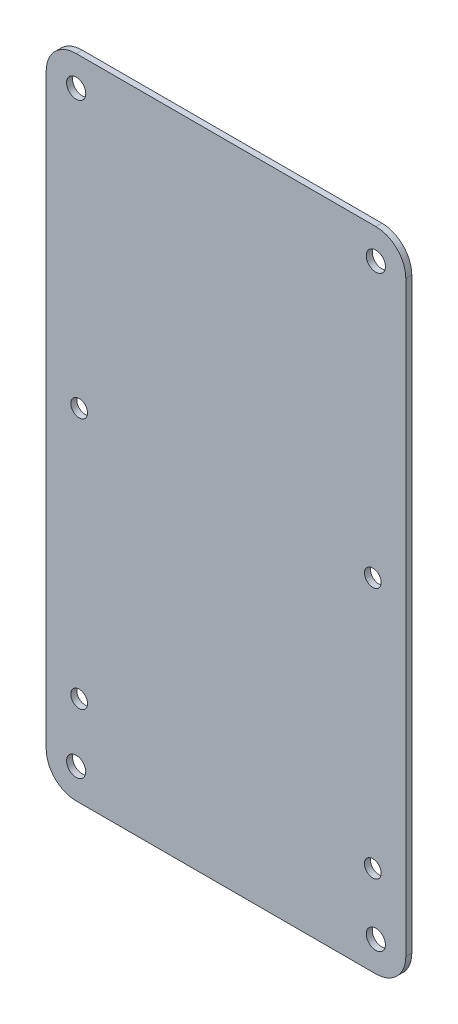
SolidWorks part; units mm, degrees
ref_plane "正面" through (0, 0, 0) normal (0, 0, 1) x (1, 0, 0)
ref_plane "平面" through (0, 0, 0) normal (0, 1, 0) x (1, 0, 0)
ref_plane "右側面" through (0, 0, 0) normal (1, 0, 0) x (0, 0, -1)
sketch "ｽｹｯﾁ1" plane through (0, 0, 0) normal (0, 0, 1) x (1, 0, 0)
  line L1 (-30, 54) -> (30, 54)
  line L2 (-30, 54) -> (-30, -54)
  line L3 (-30, -54) -> (30, -54)
  line L4 (30, 54) -> (30, -54)
  line L5 (-30, 54) -> (30, -54) construction
  line L6 (-30, -54) -> (30, 54) construction
  point P0 (0, 0)
  dimension "D1" = 60
  dimension "D2" = 108
extrude "ﾎﾞｽ - 押し出し1" add sketch "ｽｹｯﾁ1" along normal blind 1
sketch "ｽｹｯﾁ4" plane through (0, 0, 1) normal (0, 0, 1) x (1, 0, 0)
  line L0 (-30, -54) -> (30, -54) construction
  line L1 (-24.5, 3) -> (24.5, 3) construction
  line L2 (-24.5, 3) -> (-24.5, -39) construction
  line L3 (-24.5, -39) -> (24.5, -39) construction
  line L4 (24.5, 3) -> (24.5, -39) construction
  circle A0 centre (-24.5, 3) radius 1.4
  circle A1 centre (-24.5, -39) radius 1.4
  circle A2 centre (24.5, 3) radius 1.4
  circle A3 centre (24.5, -39) radius 1.4
  point P4 (0, -39)
  point P7 (0, -54)
  dimension "D5" = 2.8
  dimension "D6" = 2.8
  dimension "D7" = 2.8
  dimension "D8" = 2.8
  dimension "D1" = 49
  dimension "D2" = 42
  dimension "D3" = 0
  dimension "D4" = 15
extrude "ｶｯﾄ - 押し出し2" cut sketch "ｽｹｯﾁ4" against normal blind 10
sketch "ｽｹｯﾁ9" plane through (0, 0, 1) normal (0, 0, 1) x (1, 0, 0)
  line L0 (30, -54) -> (30, 54) construction
  line L1 (-25, -49) -> (25, -49) construction
  line L2 (-25, -49) -> (-25, 49) construction
  line L3 (-25, 49) -> (25, 49) construction
  line L4 (25, -49) -> (25, 49) construction
  line L5 (-25, -49) -> (25, 49) construction
  line L6 (-25, 49) -> (25, -49) construction
  line L8 (30, 54) -> (-30, 54) construction
  circle A0 centre (25, 49) radius 1.6
  circle A1 centre (-25, 49) radius 1.6
  circle A2 centre (-25, -49) radius 1.6
  circle A3 centre (25, -49) radius 1.6
  point P0 (0, 0)
  dimension "D3" = 3.2
  dimension "D4" = 3.2
  dimension "D5" = 3.2
  dimension "D6" = 3.2
  dimension "D1" = 5
  dimension "D2" = 5
extrude "ｶｯﾄ - 押し出し5" cut sketch "ｽｹｯﾁ9" against normal through all
fillet "ﾌｨﾚｯﾄ1" radius 5 4 edges at (-30, -54, 0.5) (30, -54, 0.5) (-30, 54, 0.5) (30, 54, 0.5)
